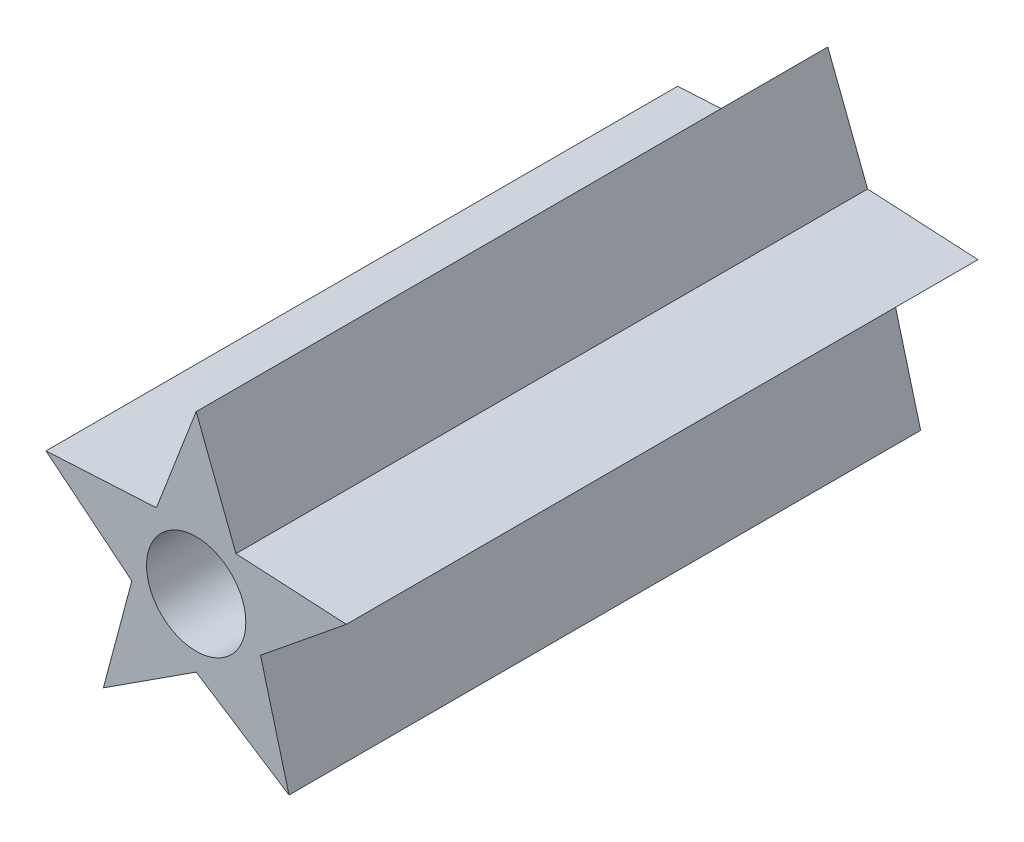
SolidWorks part; units mm, degrees
ref_plane "Front Plane" through (0, 0, 0) normal (0, 0, 1) x (1, 0, 0)
ref_plane "Top Plane" through (0, 0, 0) normal (0, 1, 0) x (1, 0, 0)
ref_plane "Right Plane" through (0, 0, 0) normal (1, 0, 0) x (0, 0, -1)
sketch "Sketch1" plane through (0, 0, 0) normal (0, 0, 1) x (1, 0, 0)
  line L0 (0, 17.5) -> (-4.4084, 6.0676)
  line L1 (10.2862, -14.1578) -> (16.6435, 5.4078) construction
  line L2 (16.6435, 5.4078) -> (0, 17.5) construction
  line L3 (0, 17.5) -> (-16.6435, 5.4078) construction
  line L4 (-16.6435, 5.4078) -> (-10.2862, -14.1578) construction
  line L5 (-10.2862, -14.1578) -> (10.2862, -14.1578) construction
  line L6 (7.1329, -2.3176) -> (4.4084, 6.0676) construction
  line L7 (4.4084, 6.0676) -> (-4.4084, 6.0676) construction
  line L8 (-4.4084, 6.0676) -> (-7.1329, -2.3176) construction
  line L9 (-7.1329, -2.3176) -> (0, -7.5) construction
  line L10 (0, -7.5) -> (7.1329, -2.3176) construction
  line L11 (-4.4084, 6.0676) -> (-16.6435, 5.4078)
  line L12 (-16.6435, 5.4078) -> (-7.1329, -2.3176)
  line L13 (-7.1329, -2.3176) -> (-10.2862, -14.1578)
  line L14 (-10.2862, -14.1578) -> (0, -7.5)
  line L15 (0, -7.5) -> (10.2862, -14.1578)
  line L16 (10.2862, -14.1578) -> (7.1329, -2.3176)
  line L17 (7.1329, -2.3176) -> (16.6435, 5.4078)
  line L18 (16.6435, 5.4078) -> (4.4084, 6.0676)
  line L19 (4.4084, 6.0676) -> (0, 17.5)
  circle A0 centre (0, 0) radius 17.5 construction
  circle A1 centre (0, 0) radius 7.5 construction
  dimension "D1" = 35
  dimension "D2" = 15
extrude "Boss-Extrude1" add sketch "Sketch1" along normal blind 70
sketch "Sketch2" plane through (0, 0, 70) normal (0, 0, 1) x (1, 0, 0)
  line L0 (16.6435, 5.4078) -> (4.4084, 6.0676) construction
  line L1 (16.6435, 5.4078) -> (4.4084, 6.0676)
  line L2 (4.4084, 6.0676) -> (3.2328, 4.4496)
  circle A0 centre (0, 0) radius 5.5
  dimension "D1" = 2
extrude "Cut-Extrude1" cut sketch "Sketch2" against normal through all contours A0
